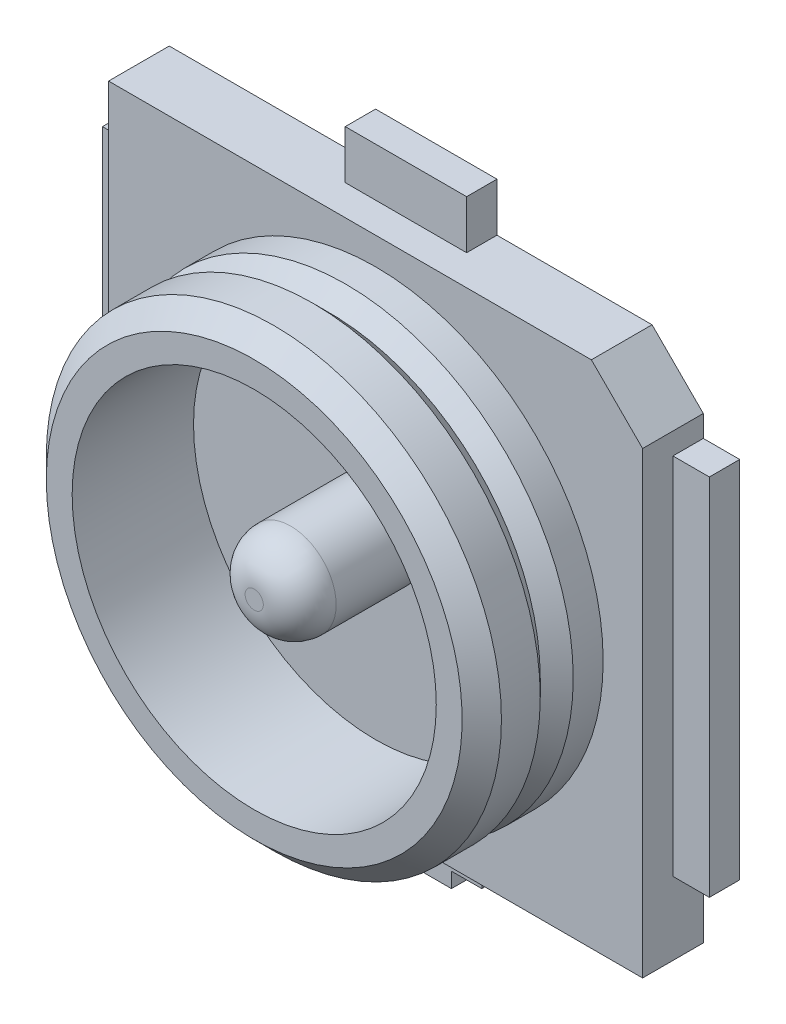
SolidWorks part; units mm, degrees
ref_plane "Front Plane" through (0, 0, 0) normal (0, 0, 1) x (1, 0, 0)
ref_plane "Top Plane" through (0, 0, 0) normal (0, 1, 0) x (1, 0, 0)
ref_plane "Right Plane" through (0, 0, 0) normal (1, 0, 0) x (0, 0, -1)
sketch "Sketch1" plane through (0, 0, 0) normal (0, 0, 1) x (1, 0, 0)
  line L0 (0.7112, 0.84) -> (0.88, 0.6712)
  line L1 (-0.88, -0.84) -> (0.88, -0.84)
  line L2 (-0.88, -0.84) -> (-0.88, 0.84)
  line L3 (-0.88, 0.84) -> (0.7112, 0.84)
  line L4 (0.88, -0.84) -> (0.88, 0.6712)
  line L5 (-0.88, -0.84) -> (0.7936, 0.7575) construction
  line L6 (-0.88, 0.84) -> (0.88, -0.84) construction
  point P0 (0, 0)
  point P1 (0, 0)
  dimension "D1" = 1.68
  dimension "D2" = 1.76
  dimension "D3" = 45
extrude "Boss-Extrude1" add sketch "Sketch1" along normal blind 0.2 contours L3 L0 L4 L1 L2
sketch "Sketch2" plane through (0, 0, 0) normal (0, 1, 0) x (1, 0, 0)
  line L0 (0.75, -0.2) -> (0.75, -0.2987)
  line L1 (-0.88, -0.2) -> (0.88, -0.2) construction
  line L2 (0.75, -0.2987) -> (0.6957, -0.353)
  line L3 (0.6957, -0.353) -> (0.75, -0.4073)
  line L4 (0.75, -0.4073) -> (0.75, -0.5352)
  line L5 (0.75, -0.5352) -> (0.6852, -0.6)
  line L6 (0.6852, -0.6) -> (0.6, -0.6)
  line L7 (0.6, -0.6) -> (0.6, -0.2)
  line L8 (0.6, -0.2) -> (0.75, -0.2)
  line L9 (-0.88, 0) -> (0.88, 0) construction
  point P13 (0.6914, -0.5882)
  point P14 (0.75, -0.587)
  dimension "D1" = 0.6
  dimension "D2" = 0.75
  dimension "D3" = 135
  dimension "D4" = 0.15
ref_axis "Axis1" through (0, 0, -0.03) along (0, 0, 1)
revolve "Revolve1" add sketch "Sketch2" angle 360 about axis through (0, 0, -0.03) along (0, 0, 1)
sketch "Sketch3" plane through (0, 0, 0.2) normal (0, 0, 1) x (1, 0, 0)
  circle A0 centre (0, 0) radius 0.15
  dimension "D1" = 0.3
extrude "Boss-Extrude2" add sketch "Sketch3" along normal blind 0.4
fillet "Fillet1" radius 0.12 1 edges at (0.15, 0, 0.6)
sketch "Sketch4" plane through (0, 0, 0) normal (0, 0, 1) x (1, 0, 0)
  line L0 (-0.88, 0.84) -> (0.7112, 0.84) construction
  line L1 (-0.2, 0.84) -> (0.2, 0.84)
  line L2 (-0.2, 0.84) -> (-0.2, 1)
  line L3 (-0.2, 1) -> (0.2, 1)
  line L4 (0.2, 0.84) -> (0.2, 1)
  line L5 (-0.88, -0.84) -> (0.88, -0.84) construction
  line L6 (-0.25, -0.84) -> (0.25, -0.84)
  line L7 (-0.25, -0.84) -> (-0.25, -0.95)
  line L8 (-0.15, -1) -> (0.15, -1)
  line L9 (0.25, -0.84) -> (0.25, -0.95)
  line L10 (-0.25, -0.95) -> (-0.15, -0.95)
  line L11 (-0.15, -0.95) -> (-0.15, -1)
  line L12 (0.25, -0.95) -> (0.15, -0.95)
  line L13 (0.15, -0.95) -> (0.15, -1)
  line L14 (-0.88, -0.84) -> (-0.88, 0.84) construction
  line L15 (-0.88, 0.6) -> (-1, 0.6)
  line L16 (-0.88, 0.6) -> (-0.88, -0.6)
  line L17 (-0.88, -0.6) -> (-1, -0.6)
  line L18 (-1, 0.6) -> (-1, -0.6)
  line L19 (0, 0.84) -> (0, 0) construction
  line L20 (0.88, -0.6) -> (1, -0.6)
  line L21 (1, 0.6) -> (1, -0.6)
  line L22 (0.88, 0.6) -> (1, 0.6)
  line L23 (0.88, 0.6) -> (0.88, -0.6)
  point P6 (0, 1)
  point P14 (0, -1)
  point P27 (-1, 0)
  dimension "D1" = 0.4
  dimension "D2" = 0.16
  dimension "D3" = 0.5
  dimension "D4" = 1.2
  dimension "D5" = 0.1
  dimension "D6" = 0.05
  dimension "D7" = 0.1
  dimension "D8" = 0.12
extrude "Boss-Extrude3" add sketch "Sketch4" along normal blind 0.1
